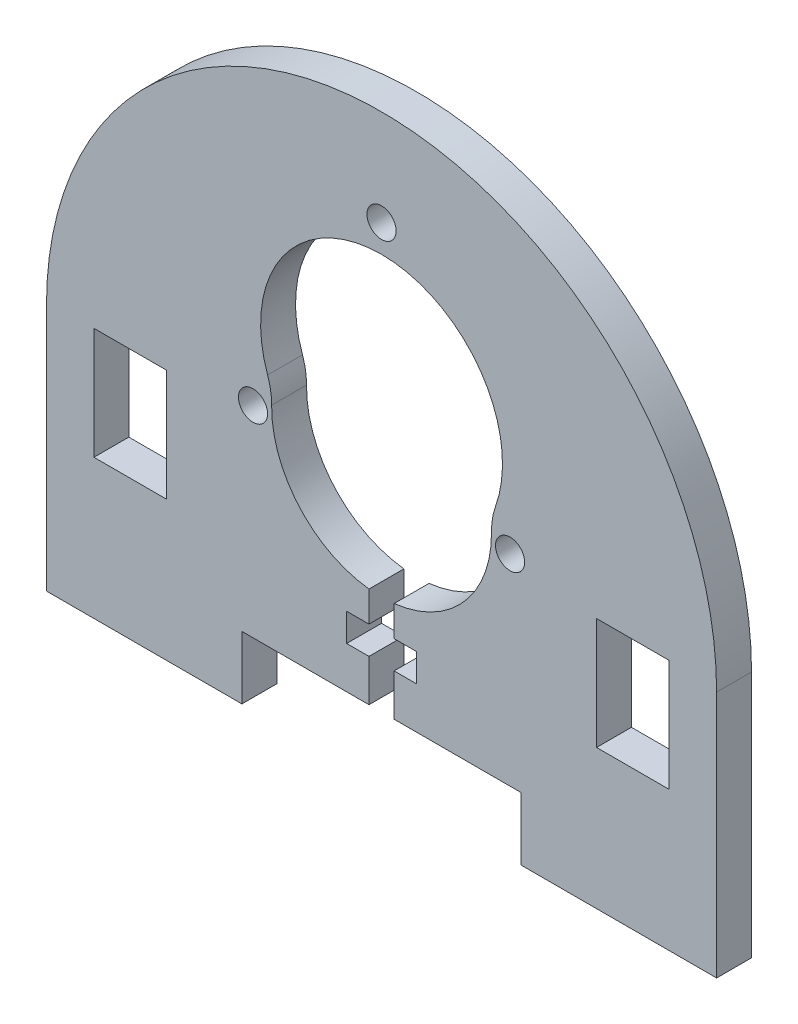
SolidWorks part; units mm, degrees
ref_plane "Front Plane" through (0, 0, 0) normal (0, 0, 1) x (1, 0, 0)
ref_plane "Top Plane" through (0, 0, 0) normal (0, 1, 0) x (1, 0, 0)
ref_plane "Right Plane" through (0, 0, 0) normal (1, 0, 0) x (0, 0, -1)
sketch "Sketch1" plane through (0, 0, 0) normal (0, 0, 1) x (1, 0, 0)
  line L0 (-30.48, 19.5049) -> (30.48, 19.5049) construction
  line L1 (30.48, -11.2601) -> (-30.48, -11.2601)
  line L2 (30.48, -11.2601) -> (30.48, 11.2601)
  line L3 (30.48, 11.2601) -> (-30.48, 11.2601) construction
  line L4 (-30.48, -11.2601) -> (-30.48, 11.2601)
  line L5 (30.48, -11.2601) -> (-30.48, 11.2601) construction
  line L6 (30.48, 11.2601) -> (-30.48, -11.2601) construction
  line L7 (0, 41.7401) -> (0, -11.2601) construction
  arc A0 (-30.48, 11.2601) -> (30.48, 11.2601) centre (0, 11.2601) cw
  circle A3 centre (0, 19.5049) radius 16.5 construction
  circle A4 centre (0, 25.5049) radius 2.5 construction
  point P0 (0, 0)
  dimension "D2" = 33
  dimension "D4" = 5
  dimension "D1" = 30.765
  dimension "D3" = 6
  dimension "D5" = 60.96
  dimension "D6" = 22.2352
extrude "Boss-Extrude1" add sketch "Sketch1" along normal blind 3.175
sketch "Sketch2" plane through (0, 0, 3.175) normal (0, 0, 1) x (1, 0, 0)
  circle A0 centre (0, 19.5049) radius 11
  dimension "D1" = 22
extrude "Cut-Extrude1" cut sketch "Sketch2" against normal up to next
sketch "Sketch3" plane through (0, 0, 3.175) normal (0, 0, 1) x (1, 0, 0)
  line L0 (30.48, -11.2601) -> (-30.48, -11.2601) construction
  line L1 (-12.7, -11.2601) -> (12.7, -11.2601)
  line L2 (-12.7, -11.2601) -> (-12.7, -5.5451)
  line L3 (-12.7, -5.5451) -> (12.7, -5.5451)
  line L4 (12.7, -11.2601) -> (12.7, -5.5451)
  line L6 (0, 41.7401) -> (0, -11.2601) construction
  point P6 (0, -5.5451)
  dimension "D1" = 5.715
  dimension "D2" = 25.4
extrude "Cut-Extrude2" cut sketch "Sketch3" against normal up to next
sketch "Sketch4" plane through (0, 0, 3.175) normal (0, 0, 1) x (1, 0, 0)
  line L0 (-30.48, -11.2601) -> (-12.7, -11.2601) construction
  line L1 (30.48, -11.2601) -> (-30.48, -11.2601) construction
  line L2 (-12.7, -5.5451) -> (-12.7, -11.2601) construction
  line L3 (-22.8266, -1014.3325) -> (-22.8266, 48985.6675) construction
  line L4 (0, -1.7463) -> (0, 1.7463) construction
  line L5 (-21.2391, 3.9799) -> (-24.4141, 3.9799)
  line L6 (-21.2391, 3.9799) -> (-21.2391, 10.3299)
  line L7 (-21.2391, 10.3299) -> (-24.4141, 10.3299)
  line L8 (-24.4141, 3.9799) -> (-24.4141, 10.3299)
  line L9 (-21.2391, 3.9799) -> (-24.4141, 10.3299) construction
  line L10 (-21.2391, 10.3299) -> (-24.4141, 3.9799) construction
  line L11 (21.2391, 1.4399) -> (24.4141, -4.9101) construction
  line L12 (-21.2391, -4.9101) -> (-24.4141, -4.9101)
  line L13 (-21.2391, -4.9101) -> (-21.2391, 1.4399)
  line L14 (-21.2391, 1.4399) -> (-24.4141, 1.4399)
  line L15 (-24.4141, -4.9101) -> (-24.4141, 1.4399)
  line L16 (-21.2391, -4.9101) -> (-24.4141, 1.4399) construction
  line L17 (-21.2391, 1.4399) -> (-24.4141, -4.9101) construction
  line L18 (21.2391, -4.9101) -> (24.4141, 1.4399) construction
  line L19 (21.2391, 10.3299) -> (24.4141, 3.9799) construction
  line L20 (21.2391, 3.9799) -> (24.4141, 10.3299) construction
  line L21 (24.4141, -4.9101) -> (24.4141, 1.4399)
  line L22 (21.2391, 1.4399) -> (24.4141, 1.4399)
  line L23 (21.2391, -4.9101) -> (21.2391, 1.4399)
  line L24 (21.2391, -4.9101) -> (24.4141, -4.9101)
  line L25 (24.4141, 3.9799) -> (24.4141, 10.3299)
  line L26 (21.2391, 10.3299) -> (24.4141, 10.3299)
  line L27 (21.2391, 3.9799) -> (21.2391, 10.3299)
  line L28 (21.2391, 3.9799) -> (24.4141, 3.9799)
  point P7 (-22.8266, -11.2601)
  point P9 (-22.8266, 7.1549)
  point P17 (-22.8266, -1.7351)
  point P23 (-21.59, -11.2601)
  point P35 (22.8266, -1.7351)
  point P36 (22.8266, 7.1549)
  dimension "D1" = 6.35
  dimension "D2" = 6.35
  dimension "D3" = 3.175
  dimension "D4" = 3.175
  dimension "D5" = 6.35
  dimension "D6" = 2.54
  dimension "D7" = 1.2366
extrude "Cut-Extrude3" [suppressed] cut sketch "Sketch4" against normal up to next
sketch "Sketch5" plane through (0, 0, 3.175) normal (0, 0, 1) x (1, 0, 0)
  line L0 (0, 41.7401) -> (0, -11.2601) construction
  line L1 (3.175, -1.7351) -> (1.143, -1.7351)
  line L2 (3.175, -1.7351) -> (3.175, 0.8049)
  line L3 (3.175, 0.8049) -> (1.143, 0.8049)
  line L4 (-3.175, -1.7351) -> (-3.175, 0.8049)
  line L5 (3.175, -1.7351) -> (-3.175, 0.8049) construction
  line L6 (3.175, 0.8049) -> (-3.175, -1.7351) construction
  line L7 (12.7, -5.5451) -> (-12.7, -5.5451) construction
  line L8 (-1.143, 0.8049) -> (-3.175, 0.8049)
  line L9 (-1.143, -5.5451) -> (1.143, -5.5451)
  line L10 (-1.143, -5.5451) -> (-1.143, -1.7351)
  line L11 (-1.143, 9.6949) -> (1.143, 9.6949)
  line L12 (1.143, -5.5451) -> (1.143, -1.7351)
  line L13 (-1.143, 0.8049) -> (-1.143, 9.6949)
  line L14 (1.143, 0.8049) -> (1.143, 9.6949)
  line L15 (-1.143, -1.7351) -> (-3.175, -1.7351)
  point P0 (0, -0.4651)
  point P14 (0, 9.6949)
  dimension "D1" = 6.35
  dimension "D2" = 2.54
  dimension "D3" = 3.81
  dimension "D4" = 2.286
  dimension "D5" = 15.24
extrude "Cut-Extrude4" cut sketch "Sketch5" against normal up to next
sketch "Sketch6" plane through (0, 0, 0) normal (0, 0, 1) x (1, 0, 0)
  line L0 (0, 41.7401) -> (0, -11.2601) construction
  circle A0 centre (0, 33.0049) radius 1.325
  circle A1 centre (11.6913, 12.7549) radius 1.325
  circle A2 centre (-11.6913, 12.7549) radius 1.325
  point P10 (0, 19.5049)
  dimension "D1" = 2.65
  dimension "D3" = 13.5
  dimension "D2" = 3
extrude "Cut-Extrude6" cut sketch "Sketch6" along normal through all
sketch "Sketch7" plane through (0, 0, 0) normal (0, 0, 1) x (1, 0, 0)
  line L0 (0, 41.7401) -> (0, -11.2601) construction
  circle A0 centre (0, 13.5049) radius 10
  dimension "D1" = 20
  dimension "D2" = 6
extrude "Cut-Extrude7" cut sketch "Sketch7" along normal through all
fillet "Fillet1" radius 6.35 2 edges at (9.9216, 14.7549, 1.5875) (-9.9216, 14.7549, 1.5875)
sketch "Sketch8" plane through (0, 0, 3.175) normal (0, 0, 1) x (1, 0, 0)
  line L0 (-22.86, 31.4207) -> (-22.86, -11.2601) construction
  line L1 (30.48, -11.2601) -> (-30.48, -11.2601) construction
  line L2 (-30.48, -11.2601) -> (-30.48, 11.2601) construction
  line L3 (0, -1.7463) -> (0, 1.7463) construction
  line L4 (22.86, 31.4207) -> (22.86, -11.2601) construction
  line L5 (19.558, 11.5999) -> (19.558, 1.4399)
  line L6 (-26.162, 11.5999) -> (-19.558, 11.5999)
  line L7 (-26.162, 11.5999) -> (-26.162, 1.4399)
  line L8 (-26.162, 1.4399) -> (-19.558, 1.4399)
  line L9 (-19.558, 11.5999) -> (-19.558, 1.4399)
  line L10 (26.162, 1.4399) -> (19.558, 1.4399)
  line L11 (26.162, 11.5999) -> (26.162, 1.4399)
  line L12 (26.162, 11.5999) -> (19.558, 11.5999)
  arc A0 (30.48, 11.2601) -> (-30.48, 11.2601) centre (0, 11.2601) ccw construction
  point P17 (-22.86, 11.5999)
  dimension "D1" = 7.62
  dimension "D2" = 6.604
  dimension "D3" = 22.86
  dimension "D4" = 10.16
extrude "Cut-Extrude8" cut sketch "Sketch8" against normal up to next
equation "\"D2@Sketch1\"=33mm"
equation "\"D1@Sketch1\"=0.75+\"thickness0.25\"+\"motor offset\""
equation "\"t\"=0.125"
equation "\"D1@Boss-Extrude1\"=\"t\""
equation "\"D4@Sketch4\"=\"t\""
equation "\"D3@Sketch4\"=\"t\""
equation "\"motor offset\"= 6mm"
equation "\"thickness0.25\"= 0.225in"
equation "\"thickness0.125\"= 0.122in"
equation "\"motor diameter\"= 33mm"
equation "\"D3@Sketch1\"=\"motor offset\""
equation "\"D1@Sketch3\"=\"thickness0.25\""
equation "\"D2@Sketch7\"=\"motor offset\""
